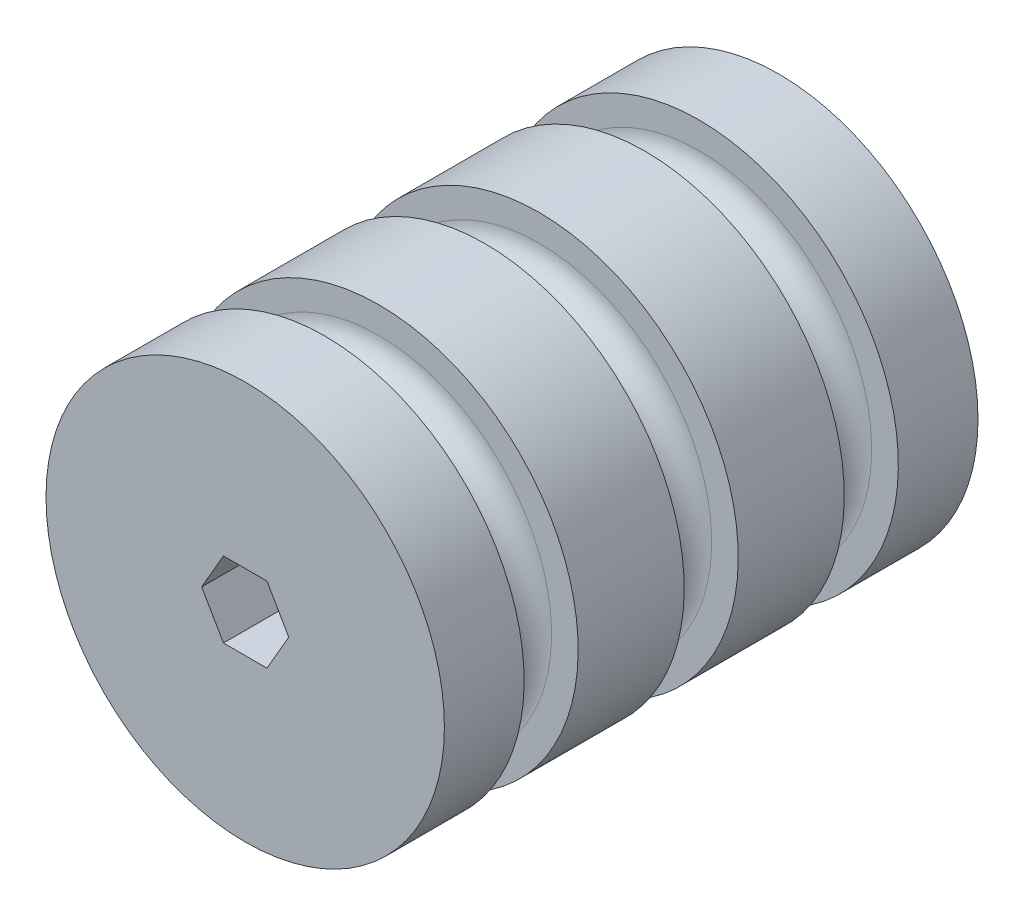
SolidWorks part; units mm, degrees
ref_plane "Front Plane" through (0, 0, 0) normal (0, 0, 1) x (1, 0, 0)
ref_plane "Top Plane" through (0, 0, 0) normal (0, 1, 0) x (1, 0, 0)
ref_plane "Right Plane" through (0, 0, 0) normal (1, 0, 0) x (0, 0, -1)
sketch "Sketch1" plane through (0, 0, 0) normal (0, 0, 1) x (1, 0, 0)
  line L0 (-3.8861, 6.731) -> (3.8861, 6.731)
  line L1 (3.8861, 6.731) -> (7.7723, 0)
  line L2 (7.7723, 0) -> (3.8861, -6.731)
  line L3 (3.8861, -6.731) -> (-3.8861, -6.731)
  line L4 (-3.8861, -6.731) -> (-7.7723, 0)
  line L5 (-7.7723, 0) -> (-3.8861, 6.731)
  line L6 (-7.7723, 0) -> (7.7723, 0) construction
  line L7 (-5.8292, -3.3655) -> (5.8292, 3.3655) construction
  line L8 (5.8292, -3.3655) -> (-5.8292, 3.3655) construction
  circle A0 centre (0, 0) radius 35.56
  point P6 (0, 0)
  dimension "D1" = 71.12
  dimension "D2" = 13.462
extrude "Boss-Extrude1" add sketch "Sketch1" along normal blind 95.25
sketch "Sketch2" plane through (0, 0, 0) normal (1, 0, 0) x (0, 0, -1)
  line L0 (0, 0) -> (-95.25, 0) construction
  line L5 (-81.026, 35.56) -> (-71.374, 35.56)
  line L8 (-81.026, 30.8102) -> (-81.026, 35.56)
  line L9 (-71.374, 30.8102) -> (-71.374, 35.56)
  line L10 (-52.451, 30.8102) -> (-52.451, 35.56)
  line L11 (-42.799, 30.8102) -> (-42.799, 35.56)
  line L12 (-23.876, 30.8102) -> (-23.876, 35.56)
  line L13 (-14.224, 30.8102) -> (-14.224, 35.56)
  line L14 (0, 35.56) -> (-95.25, 35.56) construction
  line L15 (-52.451, 35.56) -> (-42.799, 35.56)
  line L16 (-23.876, 35.56) -> (-14.224, 35.56)
  arc A3 (-81.026, 30.8102) -> (-71.374, 30.8102) centre (-76.2, 30.8102) ccw
  arc A4 (-52.451, 30.8102) -> (-42.799, 30.8102) centre (-47.625, 30.8102) ccw
  arc A5 (-23.876, 30.8102) -> (-14.224, 30.8102) centre (-19.05, 30.8102) ccw
  point P13 (-47.625, 0)
  dimension "D1" = 4.7498
  dimension "D4" = 9.652
  dimension "D5" = 28.575
  dimension "D6" = 28.575
revolve "Cut-Revolve1" cut sketch "Sketch2" angle 360 about L0
